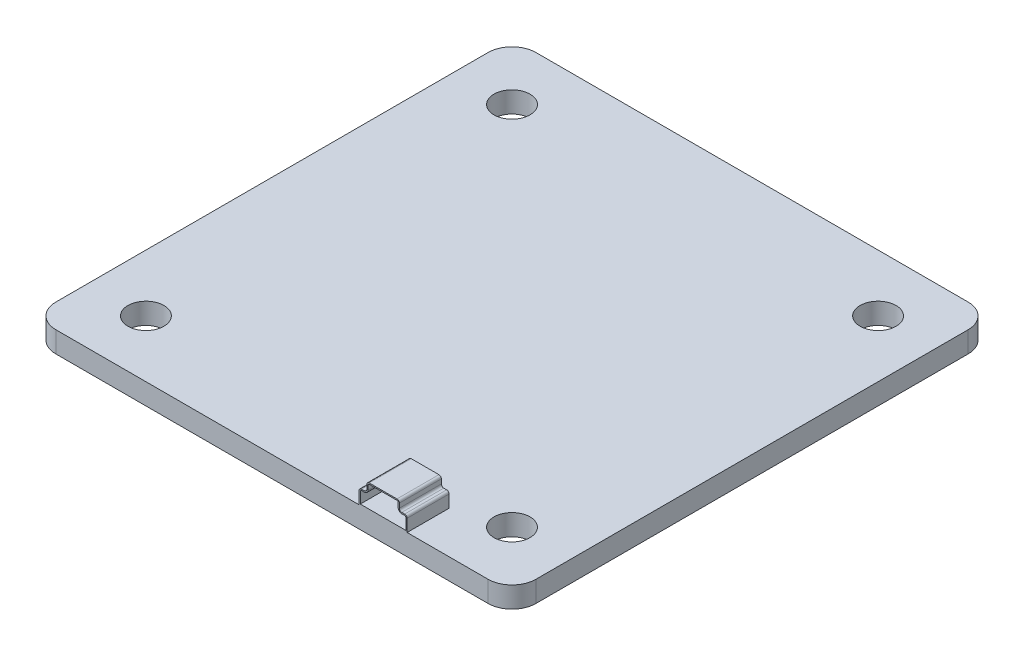
SolidWorks part; units mm, degrees
ref_plane "Front Plane" through (0, 0, 0) normal (0, 0, 1) x (1, 0, 0)
ref_plane "Top Plane" through (0, 0, 0) normal (0, 1, 0) x (1, 0, 0)
ref_plane "Right Plane" through (0, 0, 0) normal (1, 0, 0) x (0, 0, -1)
sketch "Sketch1" plane through (0, 0, 0) normal (0, 1, 0) x (1, 0, 0)
  line L1 (-18, 20) -> (18, 20)
  line L2 (-20, 18) -> (-20, -18)
  line L3 (-18, -20) -> (18, -20)
  line L4 (20, 18) -> (20, -18)
  line L5 (-20, 20) -> (20, -20) construction
  line L6 (-20, -20) -> (20, 20) construction
  line L7 (-15.25, 15.25) -> (15.25, 15.25) construction
  line L8 (-15.25, 15.25) -> (-15.25, -15.25) construction
  line L9 (-15.25, -15.25) -> (15.25, -15.25) construction
  line L10 (15.25, 15.25) -> (15.25, -15.25) construction
  line L11 (-15.25, 15.25) -> (15.25, -15.25) construction
  line L12 (-15.25, -15.25) -> (15.25, 15.25) construction
  arc A0 (18, 20) -> (20, 18) centre (18, 18) cw
  arc A1 (-20, -18) -> (-18, -20) centre (-18, -18) ccw
  arc A2 (-18, 20) -> (-20, 18) centre (-18, 18) ccw
  arc A3 (18, -20) -> (20, -18) centre (18, -18) ccw
  circle A4 centre (-15.25, 15.25) radius 1.5
  circle A5 centre (15.25, 15.25) radius 1.5
  circle A6 centre (15.25, -15.25) radius 1.5
  circle A7 centre (-15.25, -15.25) radius 1.5
  point P0 (0, 0)
  point P18 (0, 0)
  dimension "D2" = 2
  dimension "D4" = 3
  dimension "D1" = 40
  dimension "D3" = 30.5
extrude "Boss-Extrude1" add sketch "Sketch1" along normal blind 1.75
sketch "Sketch2" plane through (0, 0, 20) normal (0, 0, 1) x (1, 0, 0)
  line L0 (7.26, 1.75) -> (7.26, 2.78)
  line L1 (-18, 1.75) -> (18, 1.75) construction
  line L2 (7.46, 2.98) -> (7.705, 2.98)
  line L3 (7.905, 3.18) -> (7.905, 3.55)
  line L4 (8.105, 3.75) -> (10.415, 3.75)
  line L5 (10.615, 3.55) -> (10.615, 3.18)
  line L6 (10.815, 2.98) -> (11.06, 2.98)
  line L7 (11.26, 2.78) -> (11.26, 1.75)
  line L8 (11.26, 1.75) -> (7.26, 1.75)
  line L9 (18, 1.75) -> (18, 0) construction
  line L10 (7.36, 1.85) -> (7.36, 2.78)
  line L11 (7.46, 2.88) -> (7.705, 2.88)
  line L12 (8.005, 3.18) -> (8.005, 3.55)
  line L13 (8.105, 3.65) -> (10.415, 3.65)
  line L14 (10.515, 3.55) -> (10.515, 3.18)
  line L15 (10.815, 2.88) -> (11.06, 2.88)
  line L16 (11.16, 2.78) -> (11.16, 1.85)
  line L17 (11.16, 1.85) -> (7.36, 1.85)
  arc A0 (11.06, 2.98) -> (11.26, 2.78) centre (11.06, 2.78) cw
  arc A1 (10.615, 3.18) -> (10.815, 2.98) centre (10.815, 3.18) ccw
  arc A2 (10.415, 3.75) -> (10.615, 3.55) centre (10.415, 3.55) cw
  arc A3 (7.905, 3.55) -> (8.105, 3.75) centre (8.105, 3.55) cw
  arc A4 (7.705, 2.98) -> (7.905, 3.18) centre (7.705, 3.18) ccw
  arc A5 (7.26, 2.78) -> (7.46, 2.98) centre (7.46, 2.78) cw
  arc A6 (7.36, 2.78) -> (7.46, 2.88) centre (7.46, 2.78) cw
  arc A7 (7.705, 2.88) -> (8.005, 3.18) centre (7.705, 3.18) ccw
  arc A8 (8.005, 3.55) -> (8.105, 3.65) centre (8.105, 3.55) cw
  arc A9 (10.415, 3.65) -> (10.515, 3.55) centre (10.415, 3.55) cw
  arc A10 (10.515, 3.18) -> (10.815, 2.88) centre (10.815, 3.18) ccw
  arc A11 (11.06, 2.88) -> (11.16, 2.78) centre (11.06, 2.78) cw
  point P13 (8.5797, 3.6921)
  point P14 (8.5797, 3.4478)
  point P15 (8.3843, 5.3289)
  point P16 (10.07, 5.4511)
  point P29 (9.26, 3.75)
  point P30 (9.26, 1.75)
  dimension "D4" = 0.2
  dimension "D1" = 7.26
  dimension "D2" = 6.74
  dimension "D3" = 2
  dimension "D5" = 2.31
  dimension "D6" = 1.23
  dimension "D7" = 0.1
extrude "Boss-Extrude2" add sketch "Sketch2" against normal blind 3
sketch "Sketch3" plane through (0, 0, 17) normal (0, 0, -1) x (-1, 0, 0)
  line L8 (-11.26, 1.75) -> (-7.26, 1.75)
  line L9 (-7.26, 1.75) -> (-7.26, 2.78)
  line L10 (-7.46, 2.98) -> (-7.705, 2.98)
  line L11 (-7.905, 3.18) -> (-7.905, 3.55)
  line L12 (-8.105, 3.75) -> (-10.415, 3.75)
  line L13 (-10.615, 3.55) -> (-10.615, 3.18)
  line L14 (-10.815, 2.98) -> (-11.06, 2.98)
  line L15 (-11.26, 2.78) -> (-11.26, 1.75)
  line L16 (-11.26, 1.75) -> (-7.26, 1.75)
  line L17 (-7.26, 1.75) -> (-7.26, 2.78)
  line L18 (-7.46, 2.98) -> (-7.705, 2.98)
  line L19 (-7.905, 3.18) -> (-7.905, 3.55)
  line L20 (-8.105, 3.75) -> (-10.415, 3.75)
  line L21 (-10.615, 3.55) -> (-10.615, 3.18)
  line L22 (-10.815, 2.98) -> (-11.06, 2.98)
  line L23 (-11.26, 2.78) -> (-11.26, 1.75)
  arc A6 (-7.26, 2.78) -> (-7.46, 2.98) centre (-7.46, 2.78) ccw
  arc A7 (-7.905, 3.18) -> (-7.705, 2.98) centre (-7.705, 3.18) ccw
  arc A8 (-7.905, 3.55) -> (-8.105, 3.75) centre (-8.105, 3.55) ccw
  arc A9 (-10.415, 3.75) -> (-10.615, 3.55) centre (-10.415, 3.55) ccw
  arc A10 (-10.815, 2.98) -> (-10.615, 3.18) centre (-10.815, 3.18) ccw
  arc A11 (-11.06, 2.98) -> (-11.26, 2.78) centre (-11.06, 2.78) ccw
  arc A12 (-7.26, 2.78) -> (-7.46, 2.98) centre (-7.46, 2.78) ccw
  arc A13 (-7.905, 3.18) -> (-7.705, 2.98) centre (-7.705, 3.18) ccw
  arc A14 (-7.905, 3.55) -> (-8.105, 3.75) centre (-8.105, 3.55) ccw
  arc A15 (-10.415, 3.75) -> (-10.615, 3.55) centre (-10.415, 3.55) ccw
  arc A16 (-10.815, 2.98) -> (-10.615, 3.18) centre (-10.815, 3.18) ccw
  arc A17 (-11.06, 2.98) -> (-11.26, 2.78) centre (-11.06, 2.78) ccw
  dimension "D1" = 0
extrude "Boss-Extrude3" add sketch "Sketch3" along normal blind 0.5
sketch "Sketch4" plane through (0, 0, 16.5) normal (0, 0, -1) x (-1, 0, 0)
  line L0 (-11.26, 2.78) -> (-11.26, 1.75) construction
  line L1 (-11.26, 1.75) -> (-7.26, 1.75) construction
  circle A0 centre (-10.2, 2.87) radius 0.26
  circle A1 centre (-9.3, 2.87) radius 0.26
  circle A2 centre (-8.4, 2.87) radius 0.26
  dimension "D1" = 0.52
  dimension "D2" = 1.06
  dimension "D3" = 1.12
  dimension "D4" = 0.9
  dimension "D5" = 0.9
extrude "Cut-Extrude1" cut sketch "Sketch4" against normal through all
